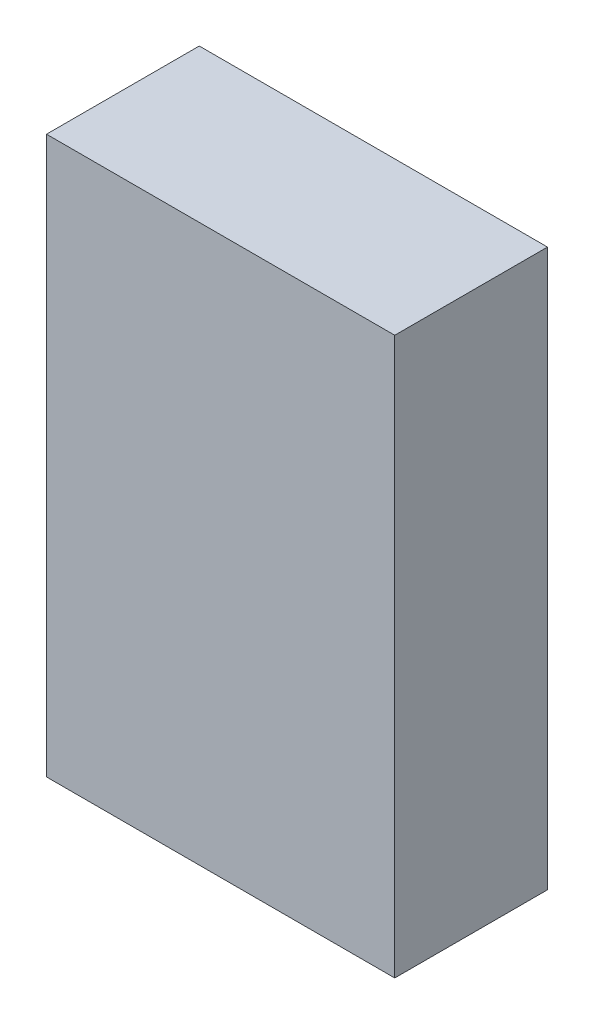
SolidWorks part; units mm, degrees
ref_plane "前视基准面" through (0, 0, 0) normal (0, 0, 1) x (1, 0, 0)
ref_plane "上视基准面" through (0, 0, 0) normal (0, 1, 0) x (1, 0, 0)
ref_plane "右视基准面" through (0, 0, 0) normal (1, 0, 0) x (0, 0, -1)
other "Configuration Table"
sketch "草图1" plane through (0, 0, 0) normal (0, 0, 1) x (1, 0, 0)
  line L0 (42.98, -20.38) -> (27.5617, -20.38) construction
  line L1 (64.1299, 121.75) -> (-23.29, 121.75)
  line L2 (64.1299, 121.75) -> (64.1299, -20.38)
  line L3 (64.1299, -20.38) -> (-23.29, -20.38)
  line L4 (-23.29, 121.75) -> (-23.29, -20.38)
  line L5 (-22.29, 116.75) -> (-22.29, 121.75) construction
  dimension "D1" = 1
extrude "凸台-拉伸1" add sketch "草图1" along normal blind 2
sketch "草图3" plane through (0, 0, 2) normal (0, 0, 1) x (1, 0, 0)
  line L0 (66.1299, -22.38) -> (66.1299, 123.75)
  line L1 (66.1299, 123.75) -> (-25.29, 123.75)
  line L2 (-25.29, 123.75) -> (-25.29, -22.38)
  line L3 (-25.29, -22.38) -> (66.1299, -22.38)
  line L4 (64.1299, -20.38) -> (64.1299, 121.75)
  line L5 (64.1299, 121.75) -> (-23.29, 121.75)
  line L6 (-23.29, 121.75) -> (-23.29, -20.38)
  line L7 (-23.29, -20.38) -> (64.1299, -20.38)
  line L8 (64.1299, -20.38) -> (64.1299, 121.75)
  line L9 (64.1299, 121.75) -> (-23.29, 121.75)
  line L10 (-23.29, 121.75) -> (-23.29, -20.38)
  line L11 (-23.29, -20.38) -> (64.1299, -20.38)
  dimension "D1" = 0
  dimension "D2" = 2
extrude "凸台-拉伸2" add sketch "草图3" against normal up to surface (40.1 mm away)
sketch "草图4" plane through (0, -22.38, 0) normal (0, -1, 0) x (1, 0, 0)
  line L8 (13.73, -15.6) -> (-13.73, -15.6)
  line L9 (-13.73, -15.6) -> (-13.73, -23.91)
  line L10 (-13.73, -23.91) -> (13.73, -23.91)
  line L11 (13.73, -23.91) -> (13.73, -15.6)
  line L12 (13.73, -15.6) -> (-13.73, -15.6)
  line L13 (-13.73, -15.6) -> (-13.73, -23.91)
  line L14 (-13.73, -23.91) -> (13.73, -23.91)
  line L15 (13.73, -23.91) -> (13.73, -15.6)
  line L16 (-15.95, -4) -> (1.95, -4)
  line L17 (1.95, -4) -> (1.95, 0)
  line L18 (1.95, 0) -> (-15.95, 0)
  line L19 (-15.95, 0) -> (-15.95, -4)
  line L20 (-15.95, -4) -> (1.95, -4)
  line L21 (1.95, -4) -> (1.95, 0)
  line L22 (1.95, 0) -> (-15.95, 0)
  line L23 (-15.95, 0) -> (-15.95, -4)
  arc A0 (31.8967, -17.4163) -> (31.8967, -22.0937) centre (26.48, -19.755) ccw construction
  arc A1 (31.8967, -22.0937) -> (31.8967, -17.4163) centre (32.78, -19.755) ccw construction
  arc A2 (31.8967, -17.4163) -> (31.8967, -22.0937) centre (26.48, -19.755) ccw
  arc A3 (31.8967, -22.0937) -> (31.8967, -17.4163) centre (32.78, -19.755) ccw
  dimension "D1" = 4
  dimension "D2" = 0
extrude "切除-拉伸1" cut sketch "草图4" against normal up to next
